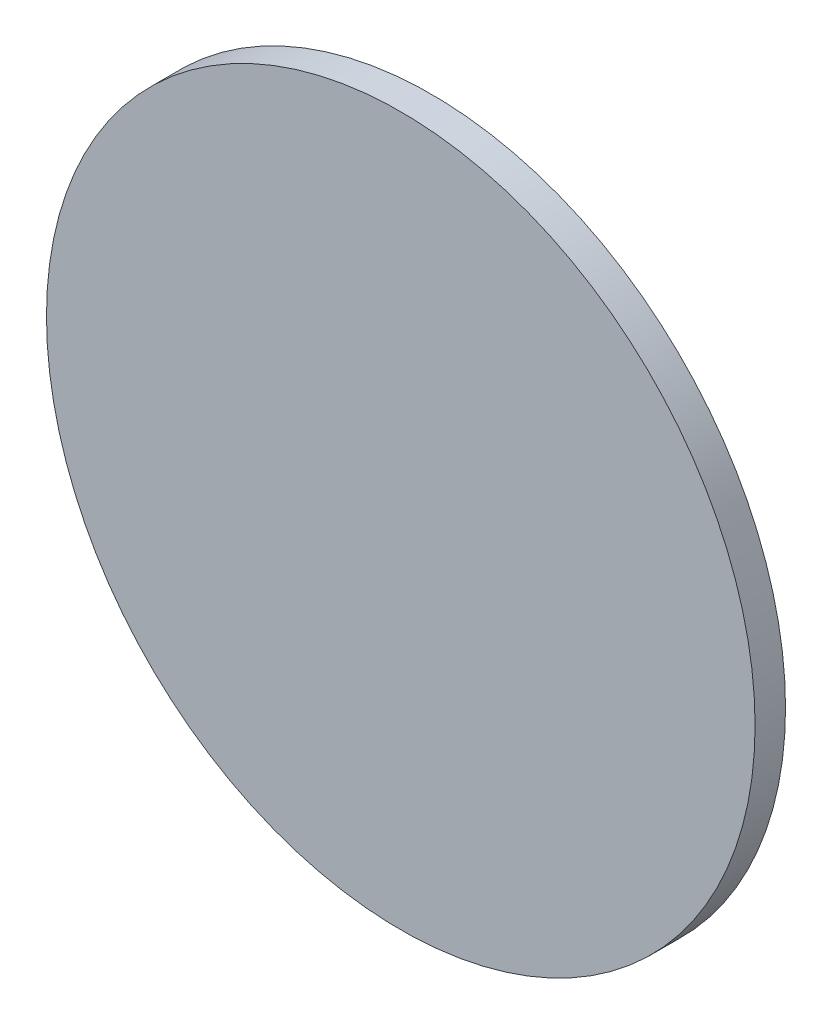
SolidWorks part; units mm, degrees
ref_plane "Plan de face" through (0, 0, 0) normal (0, 0, 1) x (1, 0, 0)
ref_plane "Plan de dessus" through (0, 0, 0) normal (0, 1, 0) x (1, 0, 0)
ref_plane "Plan de droite" through (0, 0, 0) normal (1, 0, 0) x (0, 0, -1)
sketch "Esquisse1" plane through (0, 0, 0) normal (0, 0, 1) x (1, 0, 0)
  circle A0 centre (0, 0) radius 73.914
  dimension "D1" = 147.828
extrude "Boss.-Extru.1" add sketch "Esquisse1" along normal blind 6.35
